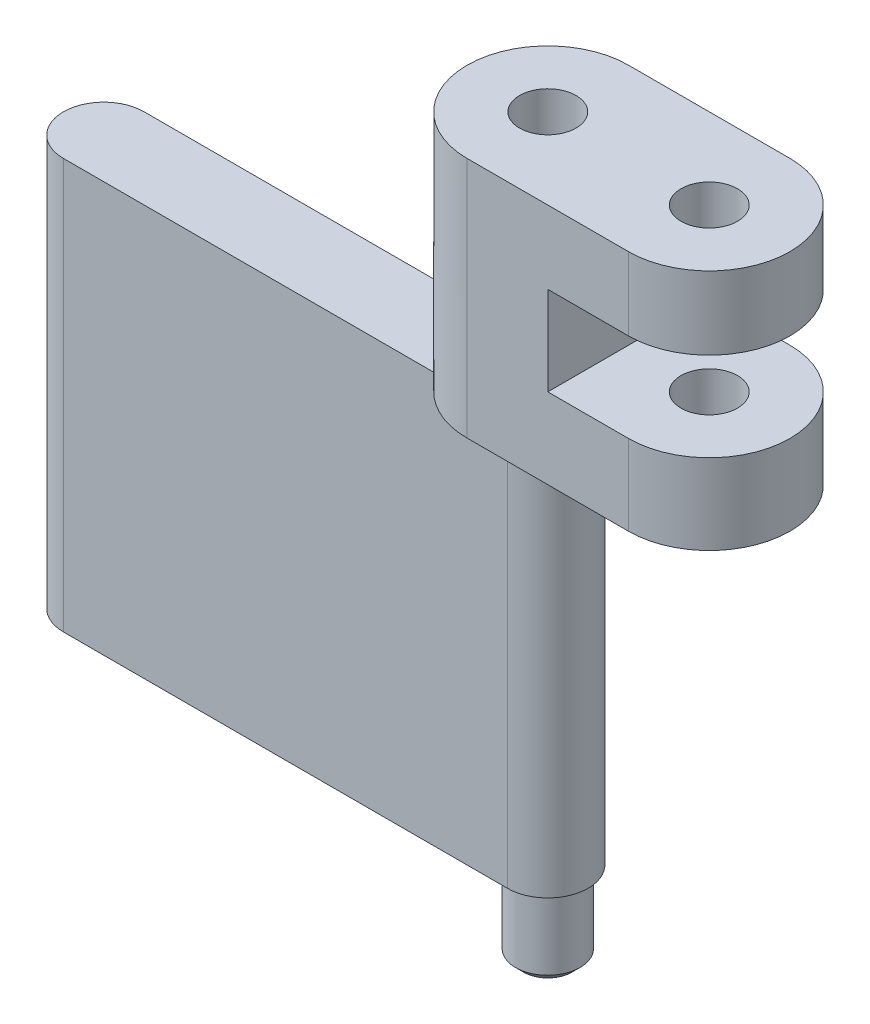
SolidWorks part; units mm, degrees
ref_plane "Front Plane" through (0, 0, 0) normal (0, 0, 1) x (1, 0, 0)
ref_plane "Top Plane" through (0, 0, 0) normal (0, 1, 0) x (1, 0, 0)
ref_plane "Right Plane" through (0, 0, 0) normal (1, 0, 0) x (0, 0, -1)
sketch "Sketch1" plane through (0, 0, 0) normal (0, 1, 0) x (1, 0, 0)
  line L0 (-10, 0) -> (10, 0) construction
  line L1 (-10, 10) -> (10, 10)
  line L2 (-10, -10) -> (10, -10)
  arc A0 (-10, 10) -> (-10, -10) centre (-10, 0) ccw
  arc A1 (10, -10) -> (10, 10) centre (10, 0) ccw
  circle A2 centre (-10, 0) radius 3.5
  circle A3 centre (10, 0) radius 3.5
  point P2 (0, 0)
  dimension "D3" = 7
  dimension "D4" = 7
  dimension "D1" = 20
  dimension "D2" = 20
extrude "Boss-Extrude1" add sketch "Sketch1" along normal blind 30
sketch "Sketch2" plane through (0, 0, 0) normal (0, -1, 0) x (1, 0, 0)
  line L0 (-10, 0) -> (-65, 0) construction
  line L1 (-10, -5) -> (-65, -5)
  line L2 (-10, 5) -> (-65, 5)
  arc A0 (-10, -5) -> (-10, 5) centre (-10, 0) ccw
  arc A1 (-65, 5) -> (-65, -5) centre (-65, 0) ccw
  point P4 (-37.5, 0)
  dimension "D1" = 55
  dimension "D2" = 10
extrude "Boss-Extrude2" add sketch "Sketch2" along normal blind 50.8
sketch "Sketch3" plane through (0, -50.8, 0) normal (0, -1, 0) x (1, 0, 0)
  line L0 (-65, -5) -> (-10, -5) construction
  circle A0 centre (-10, 0) radius 4
  arc A1 (-10, -5) -> (-10, 5) centre (-10, 0) ccw construction
  point P6 (-5, 0)
  dimension "D1" = 8
  dimension "D2" = 5
  dimension "D3" = 5
extrude "Boss-Extrude3" add sketch "Sketch3" along normal blind 10
chamfer "Chamfer1" distance 1 angle 45 1 edges at (-10, -60.8, -4)
sketch "Sketch4" plane through (0, 0, -10) normal (0, 0, -1) x (-1, 0, 0)
  line L0 (10, 30) -> (-10, 30) construction
  line L1 (-30, 20.9567) -> (0, 20.9567)
  line L2 (-30, 20.9567) -> (-30, 9.9567)
  line L3 (-30, 9.9567) -> (0, 9.9567)
  line L4 (0, 20.9567) -> (0, 9.9567)
  dimension "D1" = 11
  dimension "D2" = 9.0433
  dimension "D3" = 30
extrude "Cut-Extrude1" cut sketch "Sketch4" against normal through all
